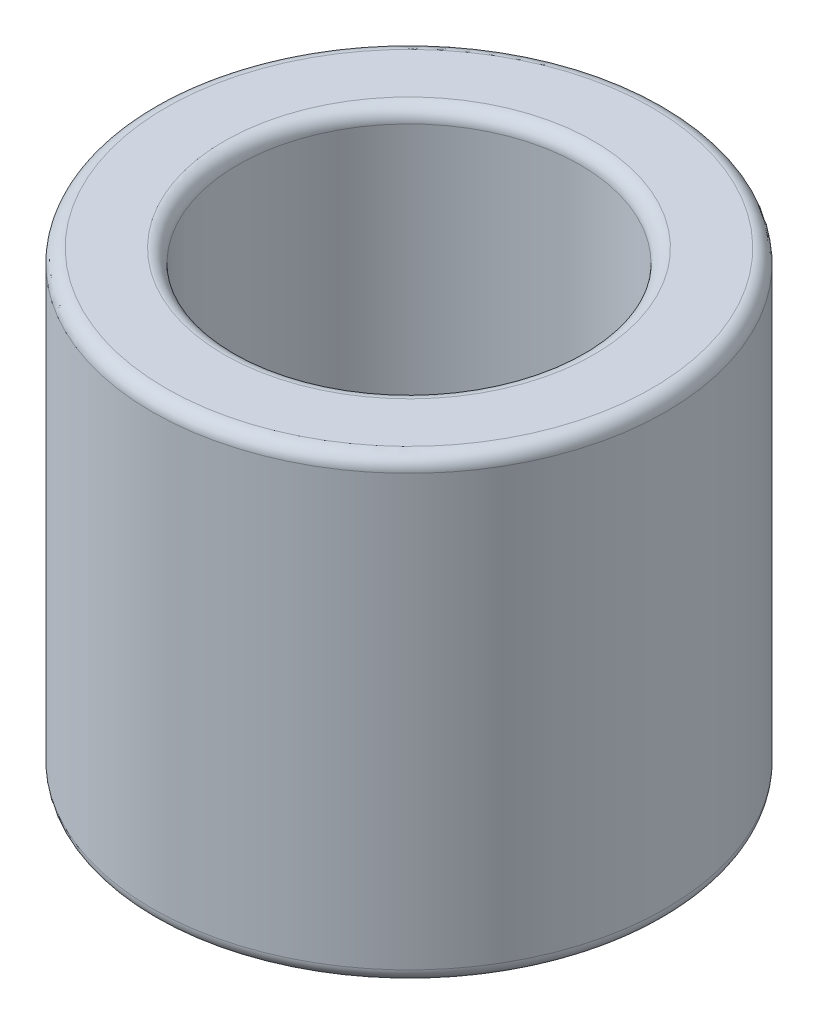
SolidWorks part; units mm, degrees
ref_plane "Front Plane" through (0, 0, 0) normal (0, 0, 1) x (1, 0, 0)
ref_plane "Top Plane" through (0, 0, 0) normal (0, 1, 0) x (1, 0, 0)
ref_plane "Right Plane" through (0, 0, 0) normal (1, 0, 0) x (0, 0, -1)
sketch "Sketch1" plane through (0, 0, 0) normal (0, 1, 0) x (1, 0, 0)
  circle A0 centre (0, 0) radius 4.7625
  circle A1 centre (0, 0) radius 3.175
  dimension "D1" = 9.525
  dimension "D2" = 6.35
extrude "Boss-Extrude1" add sketch "Sketch1" along normal blind 8.4836
fillet "Fillet1" radius 0.254 4 edges at (0, 0, 4.7625) (0, 0, 3.175) (0, 8.4836, 4.7625) (0, 8.4836, 3.175)
